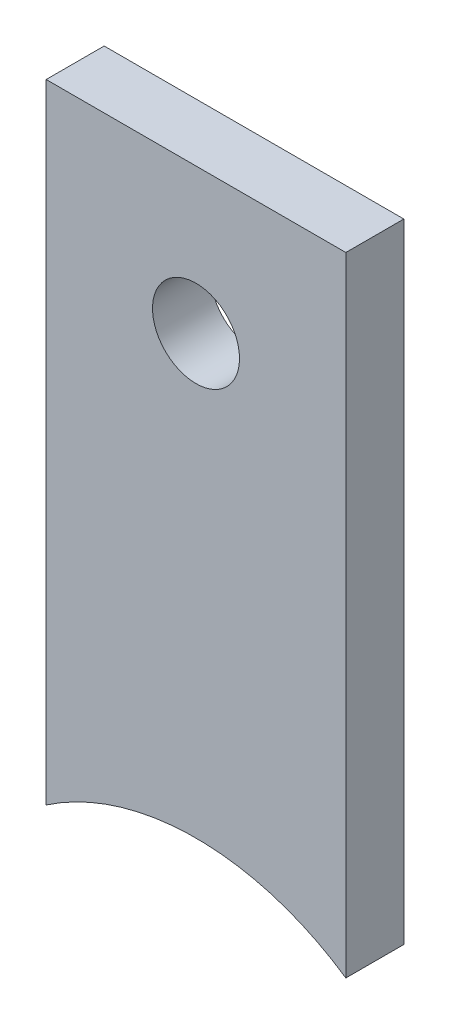
SolidWorks part; units mm, degrees
material "ASTM A36 Steel"
ref_plane "Front Plane" through (0, 0, 0) normal (0, 0, 1) x (1, 0, 0)
ref_plane "Top Plane" through (0, 0, 0) normal (0, 1, 0) x (1, 0, 0)
ref_plane "Right Plane" through (0, 0, 0) normal (1, 0, 0) x (0, 0, -1)
sketch "Sketch1" plane through (0, 0, 0) normal (0, 0, 1) x (1, 0, 0)
  line L0 (0, 146.133) -> (-62, 146.133)
  line L1 (-62, 146.133) -> (-62, 16.133)
  line L2 (0, 146.133) -> (0, 16.133)
  arc A0 (0, 16.133) -> (-62, 16.133) centre (-31, -29.2983) ccw
  dimension "D4" = 55
  dimension "D1" = 62
  dimension "D2" = 130
  dimension "D3" = 130
extrude "Boss-Extrude1" add sketch "Sketch1" along normal blind 12
sketch "Sketch2" plane through (0, 0, 12) normal (0, 0, 1) x (1, 0, 0)
  line L0 (0, 146.133) -> (-62, 146.133) construction
  circle A0 centre (-31, 116.133) radius 9
  point P4 (-31, 146.133)
  dimension "D1" = 18
  dimension "D2" = 30
  dimension "D3" = 0
extrude "Cut-Extrude1" cut sketch "Sketch2" against normal blind 12
